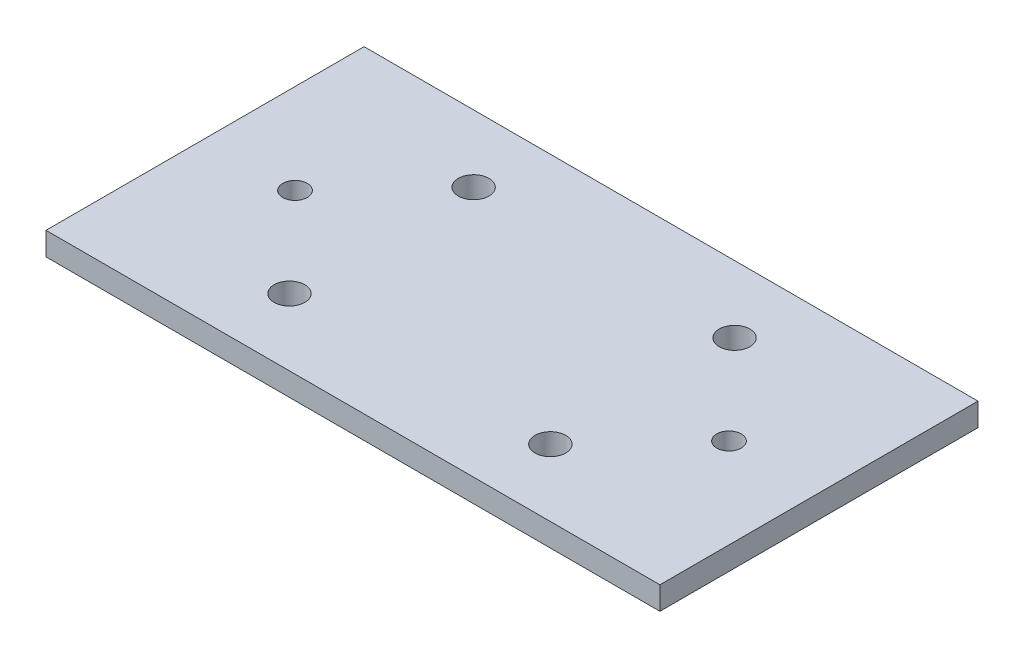
SolidWorks part; units mm, degrees
ref_plane "Front Plane" through (0, 0, 0) normal (0, 0, 1) x (1, 0, 0)
ref_plane "Top Plane" through (0, 0, 0) normal (0, 1, 0) x (1, 0, 0)
ref_plane "Right Plane" through (0, 0, 0) normal (1, 0, 0) x (0, 0, -1)
sketch "Sketch1" plane through (0, 0, 0) normal (0, 1, 0) x (1, 0, 0)
  line L0 (23, 32.7245) -> (0, 32.7245) construction
  line L1 (0, 0) -> (80, 0)
  line L2 (0, 0) -> (0, 41.449)
  line L3 (0, 41.449) -> (80, 41.449)
  line L4 (80, 0) -> (80, 41.449)
  line L5 (57, 32.7245) -> (80, 32.7245) construction
  line L6 (23, 32.7245) -> (23, 41.449) construction
  line L7 (23, 8.7245) -> (23, 0) construction
  line L8 (11.7258, 20.7245) -> (0, 20.7245) construction
  line L9 (68.2742, 20.7245) -> (80, 20.7245) construction
  circle A0 centre (23, 32.7245) radius 2
  circle A1 centre (57, 32.7245) radius 2
  circle A2 centre (23, 8.7245) radius 2
  circle A3 centre (57, 8.7245) radius 2
  circle A4 centre (11.7258, 20.7245) radius 1.6
  circle A5 centre (68.2742, 20.7245) radius 1.6
  dimension "D1" = 4
  dimension "D5" = 3.2
  dimension "D2" = 34
  dimension "D3" = 24
  dimension "D4" = 80
extrude "Boss-Extrude1" add sketch "Sketch1" along normal blind 3
